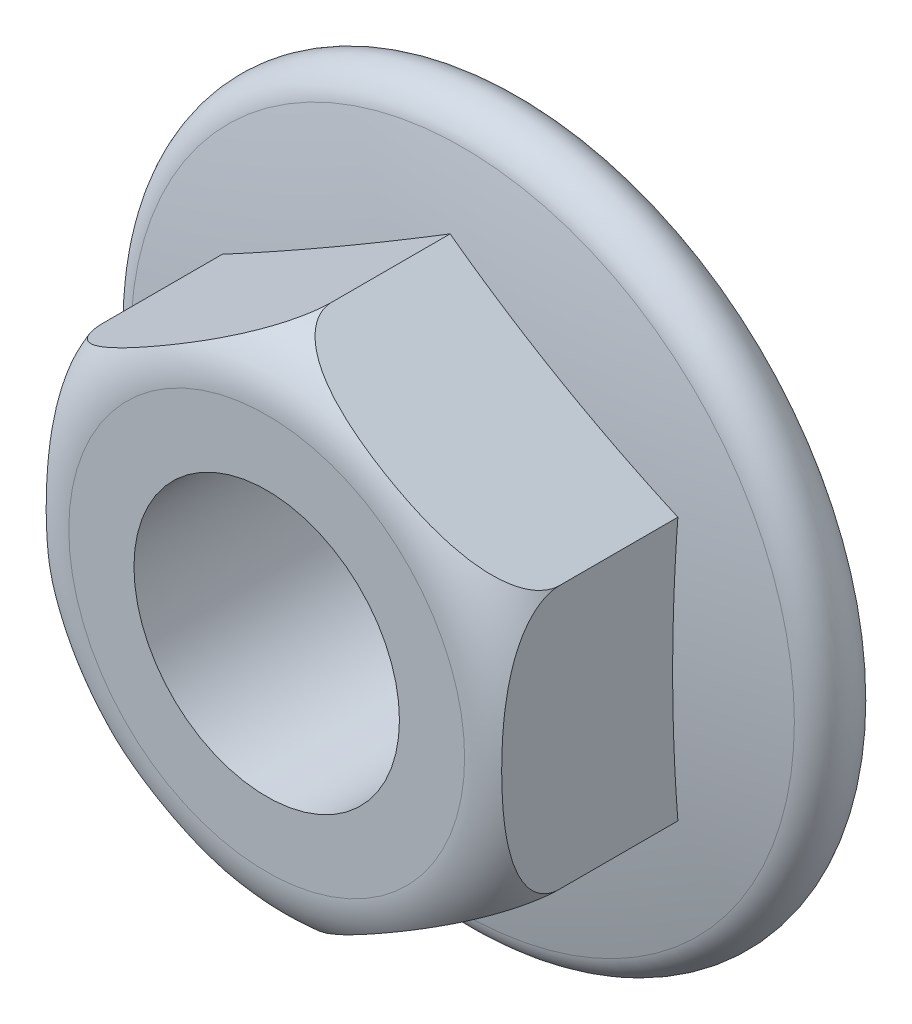
SolidWorks part; units mm, degrees
material "Plain Carbon Steel"
ref_plane "Plane1" through (0, 0, 0) normal (0, 0, 1) x (1, 0, 0)
ref_plane "Plane2" through (0, 0, 0) normal (0, 1, 0) x (-1, 0, 0)
ref_plane "Plane3" through (0, 0, 0) normal (1, 0, 0) x (0, 0, -1)
sketch "Head Sketch" plane through (0, 0, 0) normal (0, 0, 1) x (1, 0, 0)
  line L0 (0, 4.0415) -> (3.5, 2.0207)
  line L1 (3.5, 2.0207) -> (3.5, -2.0207)
  line L2 (3.5, -2.0207) -> (0, -4.0415)
  line L3 (0, -4.0415) -> (-3.5, -2.0207)
  line L4 (-3.5, -2.0207) -> (-3.5, 2.0207)
  line L5 (-3.5, 2.0207) -> (0, 4.0415)
  line L6 (3.5, 2.0207) -> (-3.5, -2.0207) construction
  line L7 (0, 4.0415) -> (0, -4.0415) construction
  line L8 (-3.5, 2.0207) -> (3.5, -2.0207) construction
  point P0 (0, 0)
  dimension "D1" = 60
  dimension "D2" = 60
  dimension "Flats" = 7
extrude "Head" add sketch "Head Sketch" along normal blind 4
sketch "Flange Sketch" plane through (0, 0, 0) normal (0, 1, 0) x (-1, 0, 0)
  line L0 (0, 1.8434) -> (0, 1.5) construction
  line L1 (-5, 0) -> (0, 0)
  line L2 (0, 50) -> (0, -50) construction
  line L4 (0, 0) -> (0, 1.5)
  line L5 (0, 0) -> (-3.5, 0) construction
  arc A0 (0, 1.5) -> (-5.099, 0.9901) centre (0, -24.25) ccw
  arc A1 (-5, 0) -> (-5.099, 0.9901) centre (-5, 0.5) cw
  dimension "D1" = 0.5
  dimension "D3" = 10
  dimension "Flange Height" = 1.5
revolve "Flange" add sketch "Flange Sketch" angle 360 about L0
sketch "Sketch5" plane through (0, 0, 0) normal (1, 0, 0) x (0, 0, -1)
  line L0 (-4, -3.0415) -> (-4, -4.0415)
  line L1 (-4, -4.0415) -> (-3, -4.0415)
  line L2 (-4, -4.0415) -> (-1.1809, -4.0415) construction
  line L3 (-4, -4.0415) -> (-4, -2.0207) construction
  line L5 (-15.0856, 0) -> (-8.1394, 0) construction
  line L6 (50, 0) -> (-50, 0) construction
  arc A0 (-4, -3.0415) -> (-3, -4.0415) centre (-3, -3.0415) ccw
  dimension "D1" = 1
revolve "Head Trim" cut sketch "Sketch5" angle 360 about L5
sketch "Hole Sketch" plane through (0, 0, 4) normal (0, 0, 1) x (1, 0, 0)
  line L0 (50, 0) -> (-50, 0) construction
  line L1 (0, -50) -> (0, 50) construction
  circle A0 centre (0, 0) radius 2.04
  dimension "Hole Dia" = 4.08
extrude "Through Hole" cut sketch "Hole Sketch" against normal through all
